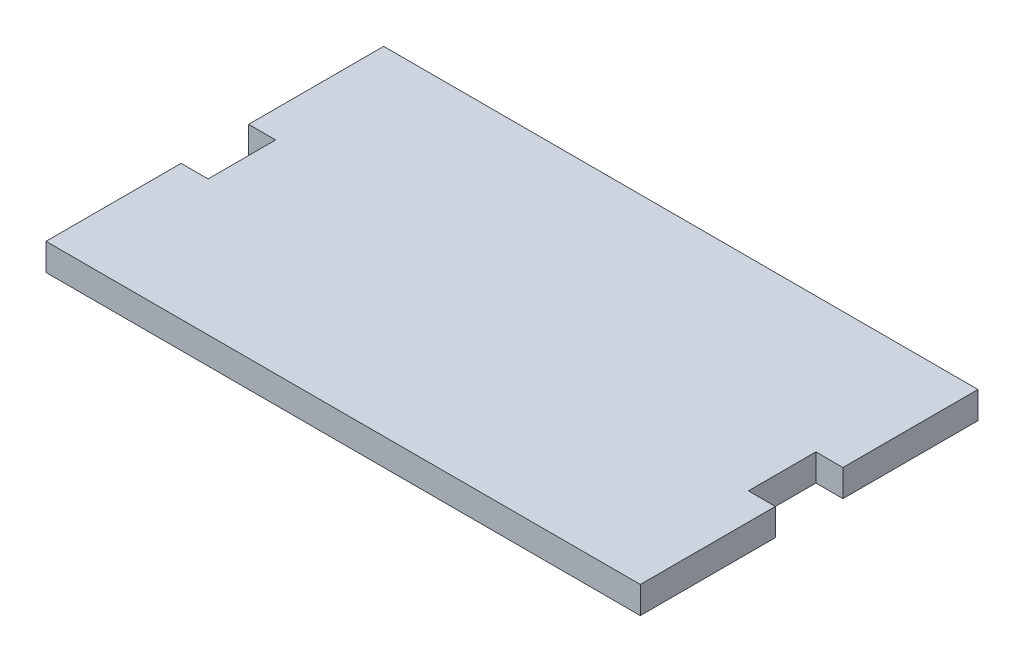
SolidWorks part; units mm, degrees
ref_plane "Front Plane" through (0, 0, 0) normal (0, 0, 1) x (1, 0, 0)
ref_plane "Top Plane" through (0, 0, 0) normal (0, 1, 0) x (1, 0, 0)
ref_plane "Right Plane" through (0, 0, 0) normal (1, 0, 0) x (0, 0, -1)
sketch "Esquisse1" plane through (0, 0, 0) normal (0, 1, 0) x (1, 0, 0)
  line L0 (-88, 30) -> (-88, 50)
  line L1 (0, 0) -> (-88, 0)
  line L2 (0, 0) -> (0, 20)
  line L3 (0, 50) -> (-88, 50)
  line L4 (-88, 0) -> (-88, 20)
  line L5 (-84, 30) -> (-88, 30)
  line L6 (-84, 30) -> (-84, 20)
  line L7 (-84, 20) -> (-88, 20)
  line L9 (0, 30) -> (0, 50)
  line L11 (-4, 30) -> (0, 30)
  line L12 (-4, 30) -> (-4, 20)
  line L13 (-4, 20) -> (0, 20)
  point P5 (-80, 15)
  point P10 (0, 15)
  dimension "D2" = 80
  dimension "D3" = 4
  dimension "D4" = 20
  dimension "D5" = 4
  dimension "D6" = 4
  dimension "D7" = 10
  dimension "D8" = 10
  dimension "D10" = 20
extrude "Boss.-Extru.1" add sketch "Esquisse1" along normal blind 4
